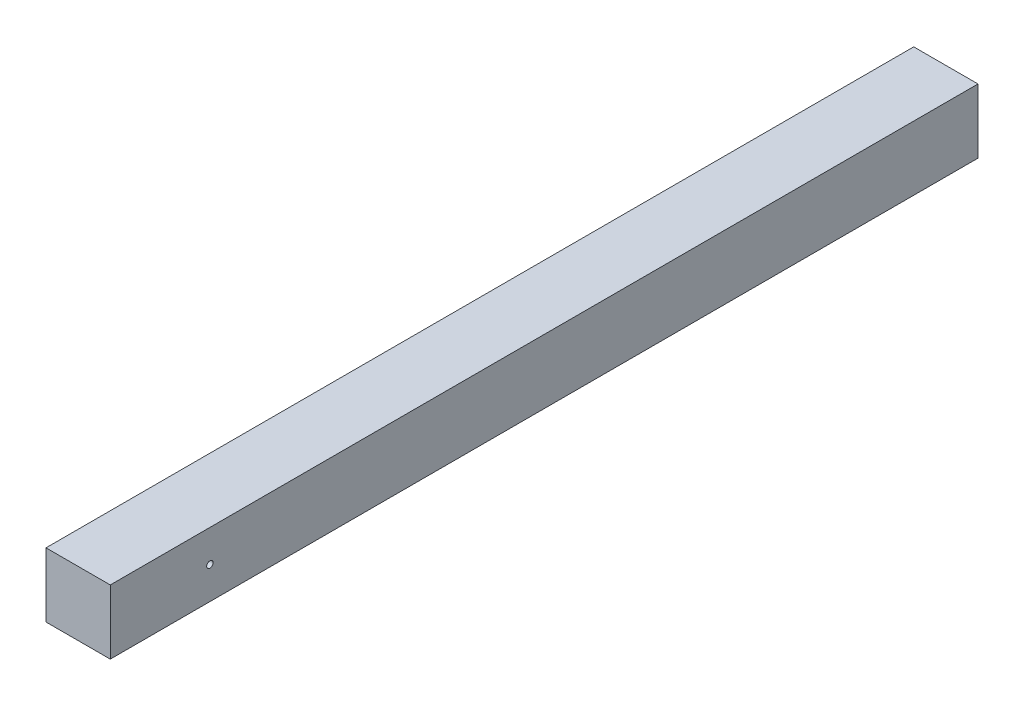
SolidWorks part; units mm, degrees
material "Pine"
ref_plane "Front Plane" through (0, 0, 0) normal (0, 0, 1) x (1, 0, 0)
ref_plane "Top Plane" through (0, 0, 0) normal (0, 1, 0) x (1, 0, 0)
ref_plane "Right Plane" through (0, 0, 0) normal (1, 0, 0) x (0, 0, -1)
sketch "Sketch1" plane through (0, 0, 0) normal (0, 0, 1) x (1, 0, 0)
  line L1 (-50, 50) -> (50, 50)
  line L2 (-50, 50) -> (-50, -50)
  line L3 (-50, -50) -> (50, -50)
  line L4 (50, 50) -> (50, -50)
  line L5 (-50, 50) -> (50, -50) construction
  line L6 (-50, -50) -> (50, 50) construction
  point P0 (0, 0)
  dimension "D1" = 100
extrude "Boss-Extrude1" add sketch "Sketch1" along normal mid plane 1350
sketch "Sketch2" plane through (-50, 0, 0) normal (-1, 0, 0) x (0, 0, 1)
  circle A0 centre (520, 0) radius 5
  dimension "D1" = 10
  dimension "D2" = 520
extrude "Cut-Extrude1" cut sketch "Sketch2" against normal through all
